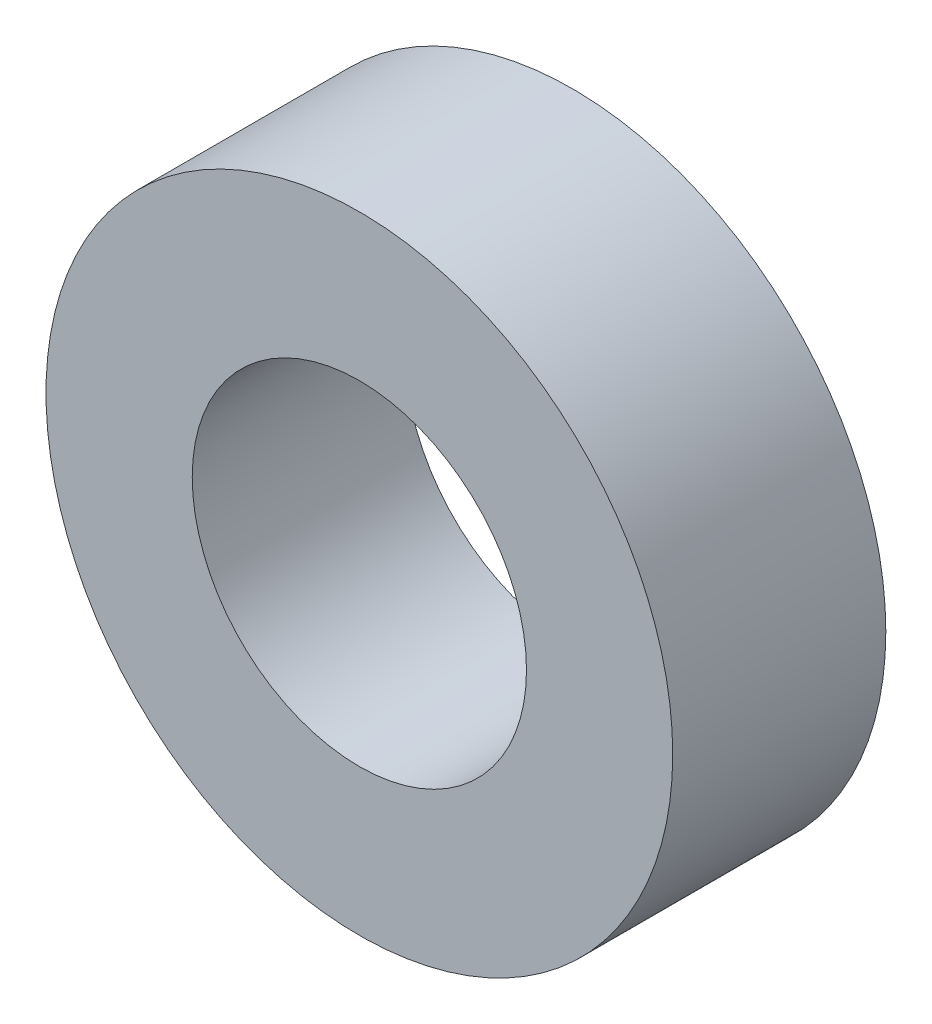
SolidWorks part; units mm, degrees
ref_plane "Front Plane" through (0, 0, 0) normal (0, 0, 1) x (1, 0, 0)
ref_plane "Top Plane" through (0, 0, 0) normal (0, 1, 0) x (1, 0, 0)
ref_plane "Right Plane" through (0, 0, 0) normal (1, 0, 0) x (0, 0, -1)
sketch "Sketch1" plane through (0, 0, 0) normal (0, 0, 1) x (1, 0, 0)
  circle A0 centre (0, 0) radius 7.5
  circle A1 centre (0, 0) radius 4
  dimension "D1" = 15
  dimension "D2" = 8
extrude "Boss-Extrude1" add sketch "Sketch1" along normal blind 5.1
